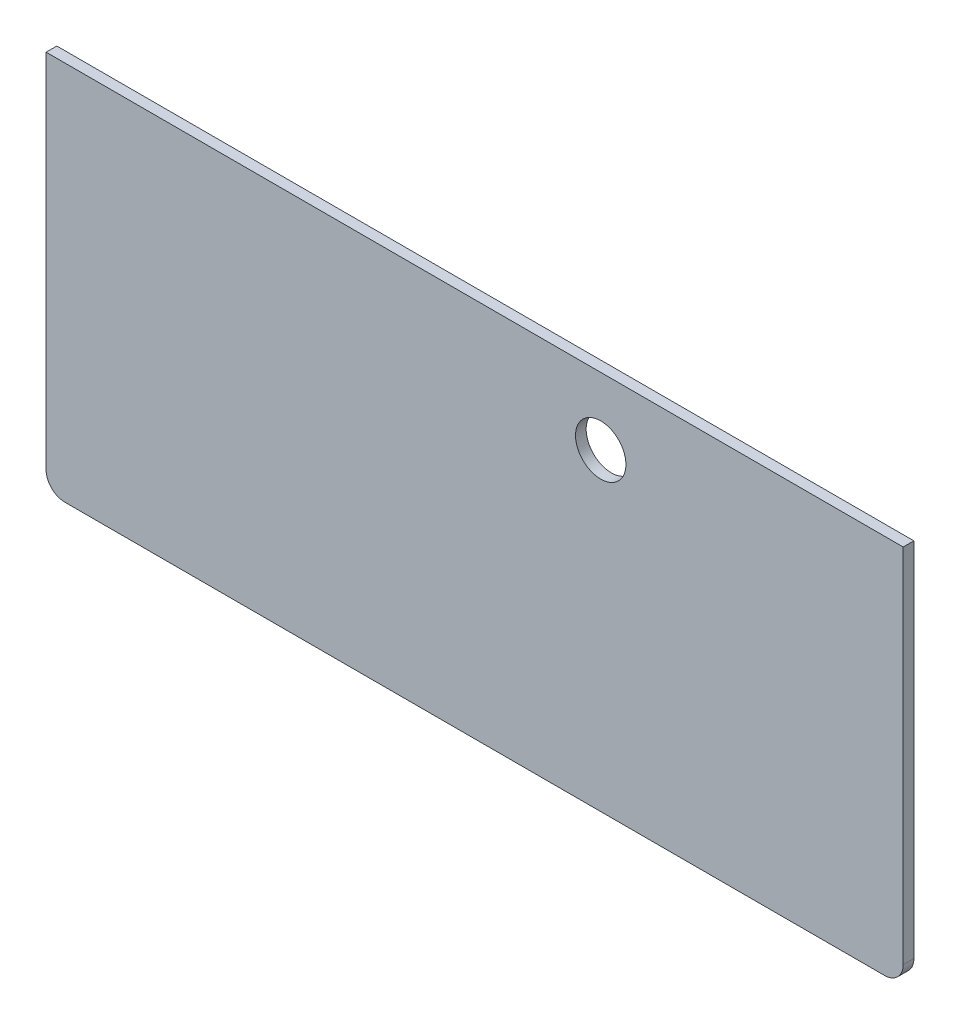
SolidWorks part; units mm, degrees
material "5052-H32"
ref_plane "Front Plane" through (0, 0, 0) normal (0, 0, 1) x (1, 0, 0)
ref_plane "Top Plane" through (0, 0, 0) normal (0, 1, 0) x (1, 0, 0)
ref_plane "Right Plane" through (0, 0, 0) normal (1, 0, 0) x (0, 0, -1)
sketch "Sketch1" plane through (0, 0, 0) normal (0, 0, 1) x (1, 0, 0)
  line L0 (-151.7654, 27.1868) -> (-151.7654, -85.9882)
  line L1 (-151.7654, -85.9882) -> (103.2346, -85.9882)
  line L2 (103.2346, -85.9882) -> (103.2346, 27.1868)
  line L3 (103.2346, 27.1868) -> (-151.7654, 27.1868)
  line L4 (13.2346, 27.1868) -> (13.2346, 7.1868) construction
  circle A0 centre (13.2346, 7.1868) radius 7.5
  dimension "D4" = 15
  dimension "D1" = 113.175
  dimension "D2" = 255
  dimension "D3" = 20
  dimension "D5" = 90
extrude "Boss-Extrude1" add sketch "Sketch1" along normal blind 3.175
fillet "Fillet1" radius 5.5562 2 edges at (-151.7654, -85.9882, 1.5875) (103.2346, -85.9882, 1.5875)
equation "\"L\"= 410mm"
equation "\"W\"= 255mm"
equation "\"H\"= 110mm"
equation "\"Compartment Width\"= 85"
equation "\"T\"= 4.7625 * 2 / 3mm"
equation "\"Inside Fillet Radius\"= 5.55625mm"
equation "\"D1@Boss-Extrude1\"=\"T\""
equation "\"D1@Fillet1\"=\"Inside Fillet Radius\""
equation "\"Hole\"=15mm"
equation "\"D4@Sketch1\"=\"Hole\""
equation "\"D2@Sketch1\"=\"W\""
equation "\"D1@Sketch1\"=\"H\"+\"T\""
